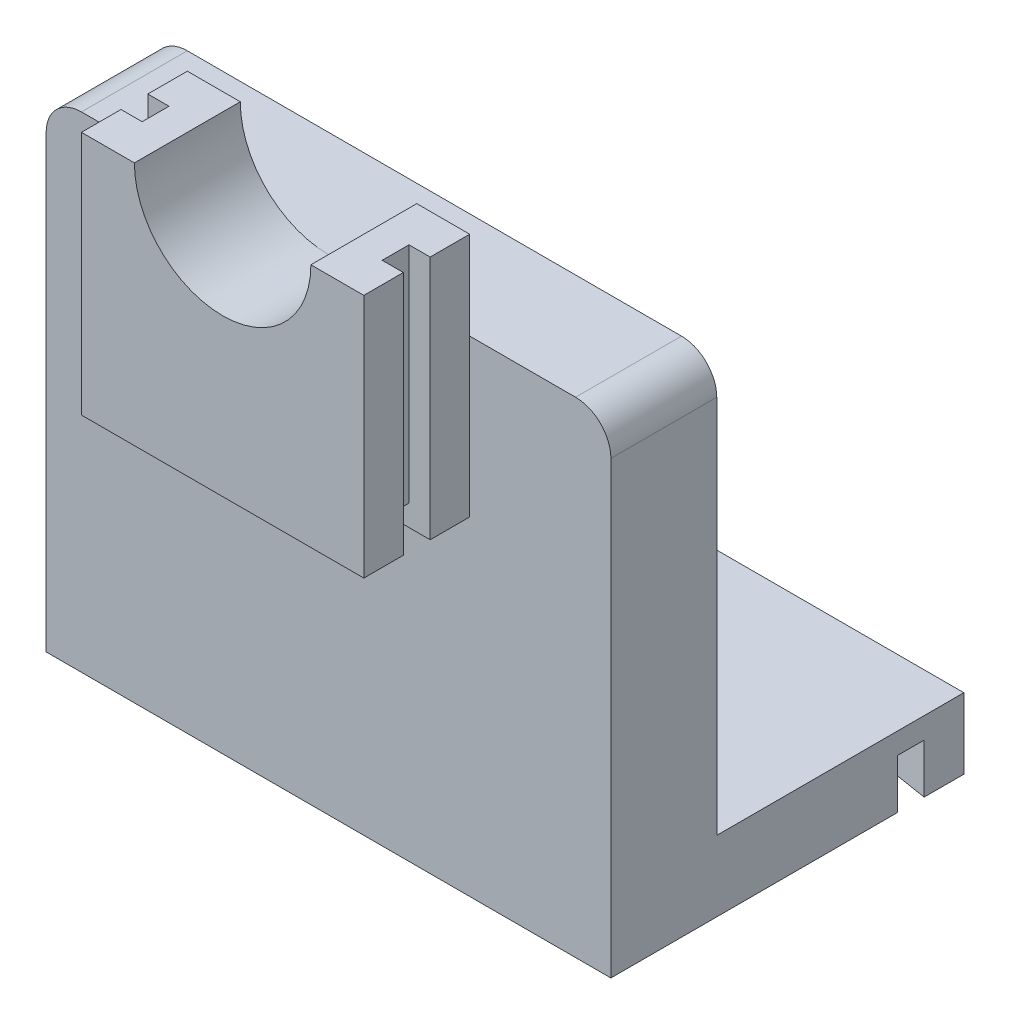
SolidWorks part; units mm, degrees
ref_plane "Front Plane" through (0, 0, 0) normal (0, 0, 1) x (1, 0, 0)
ref_plane "Top Plane" through (0, 0, 0) normal (0, 1, 0) x (1, 0, 0)
ref_plane "Right Plane" through (0, 0, 0) normal (1, 0, 0) x (0, 0, -1)
sketch "Sketch1" plane through (0, 0, 0) normal (0, 0, 1) x (1, 0, 0)
  line L0 (-109.8519, -12.5985) -> (-109.8519, -18.9485)
  line L1 (-103.5019, 55.664) -> (-14.6019, 55.664)
  line L2 (-109.8519, 49.314) -> (-109.8519, -12.5985)
  line L3 (-103.5019, -18.9485) -> (-14.6019, -18.9485)
  line L4 (-8.2519, 49.314) -> (-8.2519, -12.5985)
  line L5 (-109.8519, -18.9485) -> (-103.5019, -18.9485)
  line L6 (-14.6019, -18.9485) -> (-8.2519, -18.9485)
  line L7 (-8.2519, -18.9485) -> (-8.2519, -12.5985)
  arc A0 (-103.5019, 55.664) -> (-109.8519, 49.314) centre (-103.5019, 49.314) ccw
  arc A3 (-8.2519, 49.314) -> (-14.6019, 55.664) centre (-14.6019, 49.314) ccw
  point P6 (-109.8519, 55.664)
  point P9 (-109.8519, -18.9485)
  point P14 (-8.2519, 55.664)
  dimension "D3" = 6.35
  dimension "D1" = 74.6125
  dimension "D2" = 101.6
extrude "Boss-Extrude4" add sketch "Sketch1" along normal blind 19.05
sketch "Sketch3" plane through (0, 0, 19.05) normal (0, 0, 1) x (1, 0, 0)
  line L0 (-59.0519, 18.3578) -> (-109.8519, 18.3578) construction
  line L1 (-109.8519, -18.9485) -> (-8.2519, -18.9485) construction
  line L2 (-14.6019, 55.664) -> (-103.5019, 55.664) construction
  line L3 (-59.0519, 55.664) -> (-59.0519, -18.9485) construction
  line L4 (-84.4519, 55.664) -> (-109.8519, 55.664)
  line L5 (-33.6519, 55.664) -> (-8.2519, 55.664)
  line L7 (-84.4519, 55.664) -> (-84.4519, -18.9485) construction
  line L8 (-109.8519, 18.3578) -> (-8.2519, 18.3578) construction
  line L9 (-8.2519, -18.9485) -> (-8.2519, 49.314) construction
  line L12 (-109.8519, 27.4859) -> (-8.2519, 27.4859) construction
  line L14 (-84.4519, 27.4859) -> (-33.6519, 27.4859)
  line L15 (-84.4519, 27.4859) -> (-84.4519, 71.539)
  line L16 (-33.6519, -18.9485) -> (-33.6519, 55.664) construction
  line L17 (-84.4519, 71.539) -> (-33.6519, 71.539)
  line L18 (-33.6519, 27.4859) -> (-33.6519, 71.539)
  circle A1 centre (-59.0519, 71.539) radius 15.875
  line M7 (-14.6019, 55.664) -> (-103.5019, 55.664)
  dimension "D1" = 25.4
  dimension "D2" = 25.4
  dimension "D3" = 50.8
  dimension "D4" = 44.0531
sketch "Sketch4" plane through (0, -18.9485, 0) normal (0, -1, 0) x (-1, 0, 0)
  line L1 (8.2519, -19.05) -> (109.8519, -19.05)
  line L2 (8.2519, -19.05) -> (8.2519, 0)
  line L3 (8.2519, 0) -> (109.8519, 0)
  line L4 (109.8519, -19.05) -> (109.8519, 0)
extrude "Boss-Extrude7" add sketch "Sketch4" along normal blind 12.7
sketch "Sketch5" plane through (0, 0, 0) normal (0, 0, -1) x (-1, 0, 0)
  line L0 (109.8519, 49.314) -> (109.8519, -31.6485) construction
  line L1 (8.2519, -31.6485) -> (109.8519, -31.6485)
  line L2 (8.2519, -31.6485) -> (8.2519, -18.9485)
  line L3 (8.2519, -18.9485) -> (109.8519, -18.9485)
  line L4 (109.8519, -31.6485) -> (109.8519, -18.9485)
  dimension "D1" = 12.7
  dimension "D2" = 101.6
extrude "Boss-Extrude8" add sketch "Sketch5" along normal blind 44.45
sketch "Sketch7" plane through (0, -31.6485, 0) normal (0, -1, 0) x (1, 0, 0)
  line L0 (-8.2519, -44.45) -> (-8.2519, 19.05) construction
  line L1 (-109.8519, -44.45) -> (-8.2519, -44.45)
  line L2 (-109.8519, -44.45) -> (-109.8519, -25.4)
  line L3 (-109.8519, -25.4) -> (-8.2519, -25.4)
  line L5 (-8.2519, -44.45) -> (-8.2519, -25.4)
  line L6 (-28.0956, -38.1) -> (-16.2464, -34.925)
  line L7 (-8.2519, -38.1) -> (-109.8519, -38.1) construction
  line L8 (-16.2464, -34.925) -> (-28.0956, -31.75)
  line L9 (-8.2519, -31.75) -> (-109.8519, -31.75) construction
  line L10 (-8.2519, -34.925) -> (-109.8519, -34.925) construction
  line L11 (-84.4519, -44.45) -> (-84.4519, -25.4) construction
  line L12 (-33.6519, -44.45) -> (-33.6519, -25.4) construction
  line L13 (-28.0956, -29.3688) -> (-8.2519, -32.5437)
  line L14 (-8.2519, -32.5437) -> (-8.2519, -37.3062)
  line L15 (-8.2519, -37.3062) -> (-28.0956, -40.4812)
  line L17 (-109.8519, -37.3062) -> (-90.0081, -40.4812)
  line L18 (-109.8519, -32.5437) -> (-109.8519, -37.3062)
  line L19 (-90.0081, -29.3688) -> (-109.8519, -32.5437)
  line L20 (-101.8574, -34.925) -> (-90.0081, -31.75)
  line L21 (-90.0081, -38.1) -> (-101.8574, -34.925)
  circle A0 centre (-28.0956, -34.925) radius 3.175
  circle A1 centre (-28.0956, -34.925) radius 5.5562
  circle A2 centre (-90.0081, -34.925) radius 5.5562
  circle A3 centre (-90.0081, -34.925) radius 3.175
  dimension "D8" = 2.3813
  dimension "D1" = 19.05
  dimension "D2" = 0.7937
  dimension "D6" = 25.4
  dimension "D7" = 25.4
  dimension "D9" = 4.7625
  dimension "D10" = 31.75
extrude "Cut-Extrude1" cut sketch "Sketch7" against normal blind 8.89 contours A1 L15 L5 L13 L8 L6 | L15 A1 L6 A0 L8 L13 | L17 A2 L21 L20 L19 L2 | A3 L21 A2 L17 L19 L20
extrude "Boss-Extrude9" add sketch "Sketch3" along normal blind 19.05 contours A1 L17 L15 M7 | L14 L18 L15 M7 | A1 L18 L17 M7
sketch "Sketch9" plane through (-33.6519, 0, 0) normal (1, 0, 0) x (0, 0, -1)
  line L0 (-26.162, 71.539) -> (-30.988, 71.539)
  line L1 (-38.1, 71.539) -> (-19.05, 71.539) construction
  line L2 (-30.988, 71.539) -> (-30.988, 27.4859)
  line L3 (-38.1, 27.4859) -> (-19.05, 27.4859) construction
  line L4 (-26.162, 71.539) -> (-26.162, 27.4859)
  line L6 (-30.988, 27.4859) -> (-26.162, 27.4859)
  dimension "D1" = 7.112
  dimension "D2" = 7.112
  dimension "D3" = 4.826
extrude "Cut-Extrude2" cut sketch "Sketch9" against normal blind 3.81
sketch "Sketch10" plane through (0, 27.4859, 0) normal (0, -1, 0) x (1, 0, 0)
  line L0 (-37.4619, 30.988) -> (-84.4519, 30.988)
  line L1 (-84.4519, 38.1) -> (-84.4519, 19.05) construction
  line L2 (-37.4619, 26.162) -> (-84.4519, 26.162)
  line L3 (-84.4519, 26.162) -> (-84.4519, 30.988)
  line L4 (-37.4619, 26.162) -> (-37.4619, 30.988)
extrude "Cut-Extrude3" cut sketch "Sketch10" against normal blind 3.81
sketch "Sketch11" plane through (-84.4519, 0, 0) normal (-1, 0, 0) x (0, 0, 1)
  line L0 (30.988, 31.2959) -> (26.162, 31.2959)
  line L1 (26.162, 31.2959) -> (26.162, 71.539)
  line L2 (38.1, 71.539) -> (19.05, 71.539) construction
  line L3 (26.162, 71.539) -> (30.988, 71.539)
  line L4 (30.988, 71.539) -> (30.988, 31.2959)
extrude "Cut-Extrude4" cut sketch "Sketch11" against normal blind 3.81
